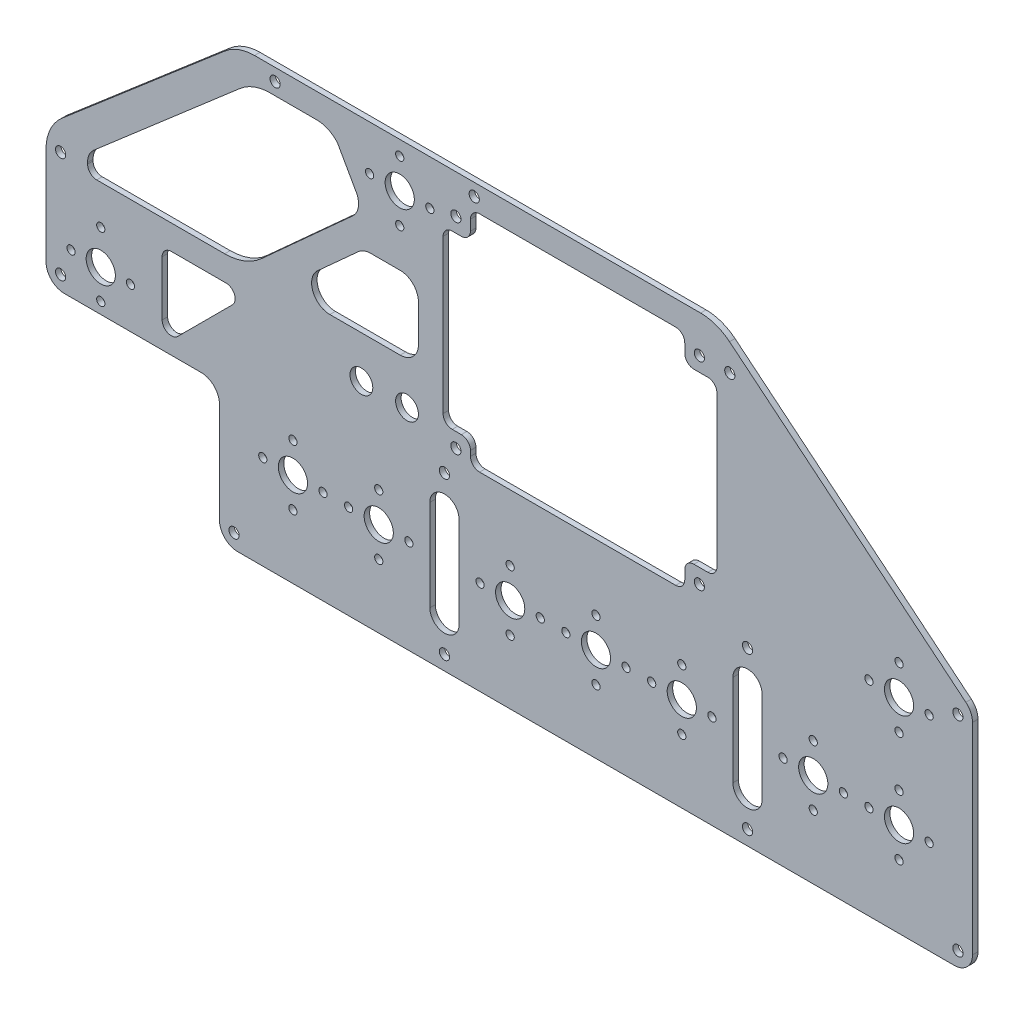
SolidWorks part; units mm, degrees
material "6061 Alloy"
ref_plane "Front Plane" through (0, 0, 0) normal (0, 0, 1) x (1, 0, 0)
ref_plane "Top Plane" through (0, 0, 0) normal (0, 1, 0) x (1, 0, 0)
ref_plane "Right Plane" through (0, 0, 0) normal (1, 0, 0) x (0, 0, -1)
sketch "Sketch1" plane through (0, 0, 0) normal (0, 1, 0) x (1, 0, 0)
  line L0 (128.905, 0.762) -> (-128.905, -0.762) construction
  line L1 (-128.905, 0.762) -> (128.905, 0.762)
  line L2 (-128.905, 0.762) -> (-128.905, -0.762)
  line L3 (-128.905, -0.762) -> (128.905, -0.762)
  line L4 (128.905, 0.762) -> (128.905, -0.762)
  dimension "D1" = 1.524
  dimension "D2" = 257.81
extrude "Boss-Extrude1" add sketch "Sketch1" along normal blind 121.92
sketch "Sketch3" plane through (0, 0, 0.762) normal (0, 0, 1) x (1, 0, 0)
  line L0 (-80.645, 5.08) -> (-80.645, 33.02)
  line L1 (-128.905, 0) -> (128.905, 0) construction
  line L2 (-85.725, 38.1) -> (-123.825, 38.1)
  line L3 (-128.905, 121.92) -> (-128.905, 0) construction
  line L4 (-128.905, 38.1) -> (-128.905, 0)
  line L5 (-124.4701, 80.0014) -> (-79.132, 118.8626)
  line L6 (-128.905, 121.92) -> (128.905, 121.92) construction
  line L7 (-128.905, 0) -> (-80.645, 0)
  line L8 (61.2988, 119.0336) -> (127.0495, 65.0242)
  line L9 (128.905, 121.92) -> (128.905, 0) construction
  line L10 (-75.565, 121.92) -> (-128.905, 121.92)
  line L11 (-128.905, 121.92) -> (-128.905, 76.2)
  line L12 (57.785, 121.92) -> (128.905, 121.92)
  line L13 (128.905, 121.92) -> (128.905, 63.5)
  line L14 (-72.517, 0) -> (-72.517, 52.324) construction
  line L15 (-72.517, 52.324) -> (-47.879, 52.324) construction
  line L16 (-47.879, 52.324) -> (-47.879, 0) construction
  line L17 (11.811, 0) -> (11.811, 52.324) construction
  line L18 (11.811, 52.324) -> (36.449, 52.324) construction
  line L19 (36.449, 52.324) -> (36.449, 0) construction
  line L20 (96.139, 0) -> (96.139, 52.324) construction
  line L21 (96.139, 52.324) -> (120.777, 52.324) construction
  line L22 (120.777, 52.324) -> (120.777, 0) construction
  line L23 (-115.5816, 76.756) -> (-74.8934, 111.9655)
  line L24 (-66.583, 115.062) -> (-53.5776, 115.062)
  line L25 (-22.098, 38.608) -> (-22.098, 13.208)
  line L26 (-43.6028, 96.883) -> (-68.9575, 73.9209)
  line L27 (-79.1876, 69.977) -> (-114.7974, 69.977)
  line L28 (-117.3374, 72.517) -> (-117.3374, 72.9146)
  line L29 (-94.0464, 63.119) -> (-78.8064, 63.119)
  line L30 (-77.0103, 58.7829) -> (-92.2503, 43.5429)
  line L31 (-96.5864, 45.339) -> (-96.5864, 60.579)
  line L32 (-38.5881, 90.3985) -> (-30.353, 90.3985)
  line L33 (-25.273, 85.3185) -> (-25.273, 75.057)
  line L34 (-30.353, 69.977) -> (-49.9188, 69.977)
  line L35 (-53.3289, 78.8224) -> (-41.9982, 89.0839)
  line L36 (-128.905, 70.3588) -> (-128.905, 43.18)
  line L37 (-8.255, 115.062) -> (46.2915, 115.062)
  line L38 (-18.415, 104.5581) -> (-18.415, 61.8725)
  line L39 (-8.255, 52.832) -> (46.2916, 52.832)
  line L40 (57.785, 104.902) -> (57.785, 62.992)
  line L41 (-70.867, 121.92) -> (53.2377, 121.92)
  line L42 (128.905, 61.0987) -> (128.905, 5.08)
  line L43 (-75.565, 0) -> (123.825, 0)
  line L44 (-47.8155, 112.4282) -> (-42.5863, 103.1407)
  line L45 (70.358, 13.208) -> (70.358, 38.608)
  line L46 (-13.97, 13.208) -> (-13.97, 38.608)
  line L47 (-15.875, 59.3325) -> (-13.335, 59.3325)
  line L48 (-10.795, 55.372) -> (-10.795, 56.7925)
  line L49 (62.23, 38.608) -> (62.23, 13.208)
  line L50 (-25.273, 75.057) -> (-25.273, 52.9255) construction
  line L51 (-15.875, 107.0981) -> (-13.335, 107.0981)
  line L52 (-10.795, 112.522) -> (-10.795, 109.6381)
  line L53 (-79.1876, 69.977) -> (-49.9188, 69.977) construction
  line L54 (-50.673, 26.162) -> (-45.847, 26.162) construction
  line L55 (55.245, 107.442) -> (51.3715, 107.442)
  line L56 (48.8315, 112.522) -> (48.8315, 109.982)
  line L57 (5.9924, 52.832) -> (122.5002, 52.832) construction
  line L59 (55.245, 60.452) -> (51.3716, 60.452)
  line L60 (48.8316, 55.372) -> (48.8316, 57.912)
  circle A0 centre (-113.665, 49.53) radius 4.064
  circle A1 centre (-113.665, 59.1295) radius 1.143
  circle A2 centre (-121.92, 49.53) radius 1.143
  circle A3 centre (-113.665, 41.275) radius 1.143
  circle A4 centre (-105.41, 49.53) radius 1.143
  circle A5 centre (-60.198, 26.162) radius 4.064
  circle A6 centre (-60.198, 34.544) radius 1.143
  circle A7 centre (-51.816, 26.162) radius 1.143
  circle A8 centre (-68.58, 26.162) radius 1.143
  circle A9 centre (-60.198, 17.78) radius 1.143
  circle A10 centre (24.13, 26.162) radius 4.064
  circle A11 centre (24.13, 34.544) radius 1.143
  circle A12 centre (24.13, 17.78) radius 1.143
  circle A13 centre (15.748, 26.162) radius 1.143
  circle A14 centre (32.512, 26.162) radius 1.143
  circle A15 centre (108.458, 26.162) radius 4.064
  circle A16 centre (108.458, 34.544) radius 1.143
  circle A17 centre (108.458, 17.78) radius 1.143
  circle A18 centre (100.076, 26.162) radius 1.143
  circle A19 centre (116.84, 26.162) radius 1.143
  arc A20 (-128.905, 70.3588) -> (-124.4701, 80.0014) centre (-116.205, 70.3588) cw
  arc A21 (-70.867, 121.92) -> (-79.132, 118.8626) centre (-70.867, 109.22) ccw
  arc A22 (53.2377, 121.92) -> (61.2988, 119.0336) centre (53.2377, 109.22) cw
  arc A23 (128.905, 61.0987) -> (127.0495, 65.0242) centre (123.825, 61.0987) ccw
  arc A24 (-80.645, 5.08) -> (-75.565, 0) centre (-75.565, 5.08) ccw
  arc A25 (-80.645, 33.02) -> (-85.725, 38.1) centre (-85.725, 33.02) ccw
  arc A26 (-128.905, 43.18) -> (-123.825, 38.1) centre (-123.825, 43.18) ccw
  arc A27 (128.905, 5.08) -> (123.825, 0) centre (123.825, 5.08) cw
  arc A28 (-74.8934, 111.9655) -> (-66.583, 115.062) centre (-66.583, 102.362) cw
  arc A29 (-47.8155, 112.4282) -> (-53.5776, 115.062) centre (-53.5776, 107.442) ccw
  arc A30 (-43.6028, 96.883) -> (-42.5863, 103.1407) centre (-47.0129, 100.6484) ccw
  arc A31 (-79.1876, 69.977) -> (-68.9575, 73.9209) centre (-79.1876, 85.217) ccw
  arc A32 (-117.3374, 72.9146) -> (-115.5816, 76.756) centre (-112.2574, 72.9146) cw
  arc A33 (-114.7974, 69.977) -> (-117.3374, 72.517) centre (-114.7974, 72.517) cw
  arc A34 (-78.8064, 63.119) -> (-77.0103, 58.7829) centre (-78.8064, 60.579) cw
  arc A35 (-92.2503, 43.5429) -> (-96.5864, 45.339) centre (-94.0464, 45.339) cw
  arc A36 (-96.5864, 60.579) -> (-94.0464, 63.119) centre (-94.0464, 60.579) cw
  arc A37 (-30.353, 69.977) -> (-25.273, 75.057) centre (-30.353, 75.057) ccw
  arc A38 (-25.273, 85.3185) -> (-30.353, 90.3985) centre (-30.353, 85.3185) ccw
  arc A39 (-38.5881, 90.3985) -> (-41.9982, 89.0839) centre (-38.5881, 85.3185) ccw
  arc A40 (-49.9188, 69.977) -> (-53.3289, 78.8224) centre (-49.9188, 75.057) cw
  arc A41 (-18.415, 104.5581) -> (-15.875, 107.0981) centre (-15.875, 104.5581) cw
  arc A42 (-13.335, 107.0981) -> (-10.795, 109.6381) centre (-13.335, 109.6381) ccw
  arc A43 (-10.795, 112.522) -> (-8.255, 115.062) centre (-8.255, 112.522) cw
  arc A44 (46.2915, 115.062) -> (48.8315, 112.522) centre (46.2915, 112.522) cw
  arc A45 (48.8315, 109.982) -> (51.3715, 107.442) centre (51.3715, 109.982) ccw
  arc A46 (55.245, 107.442) -> (57.785, 104.902) centre (55.245, 104.902) cw
  arc A47 (57.785, 62.992) -> (55.245, 60.452) centre (55.245, 62.992) cw
  arc A48 (51.3716, 60.452) -> (48.8316, 57.912) centre (51.3716, 57.912) ccw
  arc A49 (48.8316, 55.372) -> (46.2916, 52.832) centre (46.2916, 55.372) cw
  arc A50 (-8.255, 52.832) -> (-10.795, 55.372) centre (-8.255, 55.372) cw
  arc A51 (-10.795, 56.7925) -> (-13.335, 59.3325) centre (-13.335, 56.7925) ccw
  arc A52 (-15.875, 59.3325) -> (-18.415, 61.8725) centre (-15.875, 61.8725) cw
  circle A53 centre (-30.48, 109.474) radius 4.064
  circle A54 centre (-30.48, 117.856) radius 1.143
  circle A55 centre (-38.862, 109.474) radius 1.143
  circle A56 centre (-22.098, 109.474) radius 1.143
  circle A57 centre (-30.48, 101.092) radius 1.143
  circle A58 centre (-76.581, 4.064) radius 1.4224
  circle A59 centre (-18.034, 4.064) radius 1.4224
  circle A60 centre (66.294, 4.064) radius 1.4224
  circle A61 centre (124.841, 4.064) radius 1.4224
  circle A62 centre (124.841, 60.9602) radius 1.4224
  circle A63 centre (61.3657, 111.506) radius 1.4224
  circle A64 centre (-9.7543, 118.491) radius 1.4224
  circle A65 centre (-65.162, 118.491) radius 1.4224
  circle A66 centre (-124.841, 42.164) radius 1.4224
  circle A67 centre (-124.841, 71.6288) radius 1.4224
  circle A68 centre (-18.034, 47.752) radius 1.4224
  circle A69 centre (66.294, 47.752) radius 1.4224
  arc A70 (70.358, 38.608) -> (62.23, 38.608) centre (66.294, 38.608) ccw
  arc A71 (-13.97, 38.608) -> (-22.098, 38.608) centre (-18.034, 38.608) ccw
  arc A72 (-22.098, 13.208) -> (-13.97, 13.208) centre (-18.034, 13.208) ccw
  arc A73 (62.23, 13.208) -> (70.358, 13.208) centre (66.294, 13.208) ccw
  circle A74 centre (-36.322, 34.544) radius 1.143
  circle A75 centre (-36.322, 26.162) radius 4.064
  circle A76 centre (-36.322, 17.78) radius 1.143
  circle A77 centre (-27.94, 26.162) radius 1.143
  circle A78 centre (-44.704, 26.162) radius 1.143
  circle A79 centre (48.006, 26.162) radius 4.064
  circle A80 centre (48.006, 34.544) radius 1.143
  circle A81 centre (39.624, 26.162) radius 1.143
  circle A82 centre (56.388, 26.162) radius 1.143
  circle A83 centre (48.006, 17.78) radius 1.143
  circle A84 centre (0.254, 26.162) radius 4.064
  circle A85 centre (0.254, 34.544) radius 1.143
  circle A86 centre (-8.128, 26.162) radius 1.143
  circle A87 centre (8.636, 26.162) radius 1.143
  circle A88 centre (0.254, 17.78) radius 1.143
  circle A89 centre (84.582, 34.544) radius 1.143
  circle A90 centre (84.582, 26.162) radius 4.064
  circle A91 centre (76.2, 26.162) radius 1.143
  circle A92 centre (84.582, 17.78) radius 1.143
  circle A93 centre (92.964, 26.162) radius 1.143
  circle A94 centre (-28.448, 58.293) radius 3.175
  circle A95 centre (-41.148, 58.293) radius 3.175
  circle A96 centre (-14.859, 55.2685) radius 1.4224
  circle A97 centre (52.8956, 56.388) radius 1.4224
  circle A98 centre (52.8955, 111.506) radius 1.4224
  circle A99 centre (-14.859, 111.1621) radius 1.4224
  circle A100 centre (108.458, 56.896) radius 4.064
  circle A101 centre (108.458, 65.278) radius 1.143
  circle A102 centre (108.458, 48.514) radius 1.143
  circle A103 centre (100.076, 56.896) radius 1.143
  circle A104 centre (116.84, 56.896) radius 1.143
  point P114 (128.905, 0)
  point P159 (-10.795, 107.0981)
  point P168 (48.8315, 107.442)
  point P177 (48.8316, 60.452)
  point P186 (-10.795, 59.3325)
  dimension "D15" = 8.128
  dimension "D16" = 2.286
  dimension "D17" = 2.286
  dimension "D18" = 2.286
  dimension "D19" = 2.286
  dimension "D31" = 24.638
  dimension "D32" = 12.319
  dimension "D33" = 26.162
  dimension "D34" = 24.638
  dimension "D35" = 62.23
  dimension "D47" = 12.7
  dimension "D48" = 12.7
  dimension "D49" = 12.7
  dimension "D50" = 5.08
  dimension "D51" = 5.08
  dimension "D52" = 5.08
  dimension "D53" = 5.08
  dimension "D54" = 5.08
  dimension "D56" = 12.7
  dimension "D57" = 7.62
  dimension "D58" = 5.08
  dimension "D59" = 15.24
  dimension "D60" = 5.08
  dimension "D61" = 2.54
  dimension "D62" = 2.54
  dimension "D63" = 5.08
  dimension "D43" = 2.54
  dimension "D44" = 2.286
  dimension "D67" = 2.286
  dimension "D68" = 2.286
  dimension "D69" = 2.286
  dimension "D70" = 8.128
  dimension "D77" = 2.8448
  dimension "D82" = 2.8448
  dimension "D83" = 4.064
  dimension "D89" = 2.8448
  dimension "D96" = 3.429
  dimension "D97" = 3.429
  dimension "D98" = 13.97
  dimension "D101" = 2.286
  dimension "D112" = 6.35
  dimension "D113" = 6.35
  dimension "D121" = 2.8448
  dimension "D140" = 23.876
  dimension "D100" = 2.286
  dimension "D102" = 2.286
  dimension "D103" = 2.286
  dimension "D105" = 8.128
  dimension "D137" = 23.876
  dimension "D153" = 8.128
  dimension "D154" = 2.286
  dimension "D155" = 2.286
  dimension "D156" = 2.286
  dimension "D157" = 2.286
  dimension "D1" = 38.1
  dimension "D2" = 48.26
  dimension "D3" = 38.1
  dimension "D4" = 53.34
  dimension "D5" = 63.5
  dimension "D6" = 71.12
  dimension "D8" = 24.638
  dimension "D11" = 6.858
  dimension "D12" = 0.27
  dimension "D13" = 6.858
  dimension "D14" = 9.398
  dimension "D20" = 8.255
  dimension "D21" = 9.5995
  dimension "D22" = 8.255
  dimension "D23" = 8.255
  dimension "D24" = 15.24
  dimension "D25" = 11.43
  dimension "D26" = 52.324
  dimension "D27" = 52.324
  dimension "D28" = 52.324
  dimension "D29" = 4.064
  dimension "D30" = 12.319
  dimension "D36" = 76.2
  dimension "D37" = 26.162
  dimension "D38" = 8.382
  dimension "D39" = 8.382
  dimension "D40" = 8.382
  dimension "D41" = 8.382
  dimension "D45" = 6.858
  dimension "D46" = 6.858
  dimension "D55" = 71.12
  dimension "D64" = 15.24
  dimension "D65" = 15.24
  dimension "D66" = 10.414
  dimension "D71" = 8.382
  dimension "D72" = 8.382
  dimension "D73" = 8.382
  dimension "D74" = 8.382
  dimension "D75" = 12.446
  dimension "D76" = 19.685
  dimension "D78" = 4.064
  dimension "D79" = 4.064
  dimension "D84" = 4.064
  dimension "D90" = 4.064
  dimension "D91" = 4.064
  dimension "D95" = 8.128
  dimension "D99" = 1.27
  dimension "D106" = 12.319
  dimension "D107" = 23.876
  dimension "D108" = 2
  dimension "D114" = 11.684
  dimension "D115" = 11.684
  dimension "D116" = 12.7
  dimension "D117" = 23.876
  dimension "D118" = 18.288
  dimension "D119" = 18.288
  dimension "D120" = 4.064
  dimension "D122" = 4.064
  dimension "D123" = 4.064
  dimension "D125" = 4.064
  dimension "D126" = 4.064
  dimension "D129" = 4.064
  dimension "D130" = 4.064
  dimension "D131" = 4.064
  dimension "D132" = 4.064
  dimension "D133" = 4.064
  dimension "D134" = 4.064
  dimension "D135" = 7.239
  dimension "D136" = 4.064
  dimension "D138" = 18.288
  dimension "D139" = 18.288
  dimension "D141" = 84.328
  dimension "D142" = 26.162
  dimension "D143" = 26.162
  dimension "D144" = 4.064
  dimension "D145" = 4.064
  dimension "D146" = 9.144
  dimension "D147" = 25.4
  dimension "D148" = 9.144
  dimension "D149" = 9.144
  dimension "D150" = 9.144
  dimension "D151" = 84.328
  dimension "D152" = 58.547
  dimension "D158" = 8.382
  dimension "D159" = 8.382
  dimension "D160" = 8.382
  dimension "D161" = 8.382
  dimension "D42" = 3
  dimension "D80" = 2
  dimension "D81" = 2
  dimension "D85" = 2
  dimension "D86" = 2
  dimension "D87" = 2
  dimension "D88" = 2
  dimension "D92" = 2
  dimension "D93" = 2
  dimension "D94" = 2
  dimension "D104" = 2
  dimension "D109" = 2
  dimension "D110" = 2
  dimension "D111" = 2
  dimension "D124" = 2
  dimension "D127" = 2
  dimension "D128" = 2
extrude "Cut-Extrude1" cut sketch "Sketch3" against normal up to next (1.524 mm away)
